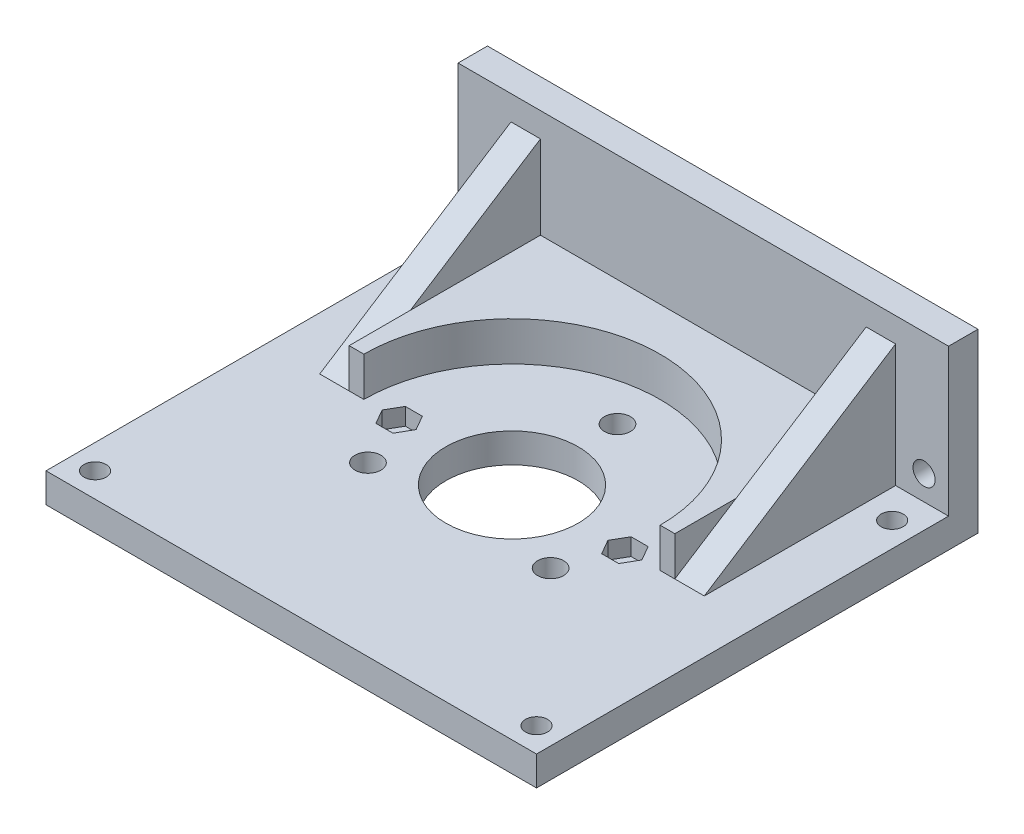
SolidWorks part; units mm, degrees
ref_plane "Front Plane" through (0, 0, 0) normal (0, 0, 1) x (1, 0, 0)
ref_plane "Top Plane" through (0, 0, 0) normal (0, 1, 0) x (1, 0, 0)
ref_plane "Right Plane" through (0, 0, 0) normal (1, 0, 0) x (0, 0, -1)
sketch "Sketch1" plane through (0, 0, 0) normal (0, 1, 0) x (1, 0, 0)
  line L0 (0, 0) -> (0, 21.5) construction
  line L1 (0, 0) -> (23.0125, 0) construction
  line L2 (-45, -40) -> (-45, -45) construction
  line L3 (50, 45) -> (-50, 45)
  line L4 (50, 45) -> (50, -45)
  line L5 (50, -45) -> (-50, -45)
  line L6 (-50, 45) -> (-50, -45)
  line L7 (-45, -40) -> (-50, -40) construction
  line L8 (-45, 32.5) -> (-50, 32.5) construction
  line L9 (-45, 32.5) -> (-45, 45) construction
  circle A0 centre (0, 0) radius 13.5
  circle A1 centre (0, 0) radius 23.0125 construction
  circle A2 centre (0, 0) radius 21.5 construction
  circle A4 centre (0, 21.5) radius 2.65
  circle A5 centre (23.0125, 0) radius 1.65
  circle A6 centre (-23.0125, 0) radius 1.65
  circle A7 centre (18.6195, -10.75) radius 2.65
  circle A8 centre (-18.6195, -10.75) radius 2.65
  circle A9 centre (-45, -40) radius 2.25
  circle A10 centre (-45, 32.5) radius 2.25
  circle A11 centre (45, 32.5) radius 2.25
  circle A12 centre (45, -40) radius 2.25
  point P24 (-50, 0)
  point P25 (0, 45)
  dimension "D1" = 27
  dimension "D2" = 46.025
  dimension "D3" = 43
  dimension "D4" = 4.5
  dimension "D5" = 5.3
  dimension "D6" = 3.3
  dimension "D9" = 5
  dimension "D11" = 12.5
  dimension "D12" = 100
  dimension "D13" = 90
  dimension "D7" = 2
  dimension "D8" = 3
extrude "Boss-Extrude1" add sketch "Sketch1" along normal blind 6
ref_plane "Plane4" through (0, 6, 0) normal (0, 1, 0) x (1, 0, 0)
sketch "Sketch2" plane through (0, 6, 0) normal (0, 1, 0) x (1, 0, 0)
  line L0 (-30.2, 0) -> (-33.2, 0)
  line L1 (-33.2, 0) -> (-33.2, 39)
  line L2 (50, 45) -> (-50, 45) construction
  line L3 (50, 45) -> (-50, 45) construction
  line L4 (-33.2, 39) -> (-33.2, 45) construction
  line L5 (-33.2, 39) -> (33.2, 39)
  line L6 (0, 0) -> (0, 9.2302) construction
  line L7 (33.2, 0) -> (33.2, 39)
  line L8 (30.2, 0) -> (33.2, 0)
  arc A0 (30.2, 0) -> (-30.2, 0) centre (0, 0) ccw
  point P13 (0, 39)
  dimension "D2" = 60.4
  dimension "D1" = 3
  dimension "D3" = 6
extrude "Boss-Extrude2" add sketch "Sketch2" along normal blind 8
sketch "Sketch3" plane through (0, 6, 0) normal (0, 1, 0) x (1, 0, 0)
  line L0 (33.2, 39) -> (-33.2, 39) construction
  line L1 (50, 39) -> (-50, 39)
  line L2 (50, 39) -> (50, 45)
  line L3 (50, 45) -> (-50, 45)
  line L4 (-50, 39) -> (-50, 45)
  line L5 (50, 45) -> (-50, 45) construction
  line L6 (33.2, 39) -> (-33.2, 39) construction
  line L7 (50, 45) -> (-50, 45) construction
  point P8 (0, 45)
  point P9 (0, 45)
extrude "Boss-Extrude3" add sketch "Sketch3" along normal blind 30
ref_plane "Plane5" through (0, 0, -39) normal (0, 0, 1) x (1, 0, 0)
sketch "Sketch7" plane through (0, 0, -39) normal (0, 0, 1) x (1, 0, 0)
  line L0 (-50, 36) -> (-50, 6) construction
  line L1 (-50, 6) -> (-33.2, 6) construction
  line L2 (-50, 36) -> (-50, 6) construction
  line L3 (-50, 6) -> (-33.2, 6) construction
  line L4 (-45, 11) -> (-50, 11) construction
  line L5 (-45, 11) -> (-45, 6) construction
  line L6 (0, 0) -> (0, 30.8351) construction
  circle A0 centre (-45, 11) radius 2.25
  circle A1 centre (45, 11) radius 2.25
  dimension "D1" = 4.5
  dimension "D2" = 5
extrude "Cut-Extrude1" cut sketch "Sketch7" against normal up to next
ref_plane "Plane6" through (0, 6, 0) normal (0, 1, 0) x (1, 0, 0)
sketch "Sketch8" plane through (0, 6, 0) normal (0, 1, 0) x (1, 0, 0)
  line L0 (19.5484, 0) -> (21.2804, -3)
  line L1 (-19.5484, 0) -> (-21.2804, 3)
  line L2 (-21.2804, 3) -> (-24.7446, 3)
  line L3 (-24.7446, 3) -> (-26.4766, 0)
  line L4 (-26.4766, 0) -> (-24.7446, -3)
  line L5 (-24.7446, -3) -> (-21.2804, -3)
  line L6 (-21.2804, -3) -> (-19.5484, 0)
  line L7 (21.2804, -3) -> (24.7446, -3)
  line L8 (24.7446, -3) -> (26.4766, 0)
  line L9 (26.4766, 0) -> (24.7446, 3)
  line L10 (24.7446, 3) -> (21.2804, 3)
  line L11 (21.2804, 3) -> (19.5484, 0)
  circle A0 centre (-23.0125, 0) radius 1.65 construction
  circle A1 centre (-23.0125, 0) radius 1.65 construction
  circle A2 centre (0, 0) radius 23.0125 construction
  circle A3 centre (-23.0125, 0) radius 3 construction
  point P6 (-23.0125, 3)
  dimension "D1" = 6
  dimension "D2" = 2
extrude "Cut-Extrude2" cut sketch "Sketch8" against normal blind 3.5
ref_plane "Plane7" through (-33.2, 0, 0) normal (-1, 0, 0) x (0, 0, 1)
sketch "Sketch9" plane through (-33.2, 0, 0) normal (-1, 0, 0) x (0, 0, 1)
  line L0 (-39, 6) -> (45, 6) construction
  line L1 (-39, 36) -> (-39, 6) construction
  line L2 (-39, 6) -> (45, 6) construction
  line L3 (-39, 36) -> (-39, 6) construction
  line L4 (0, 14) -> (0, 6) construction
  line L5 (0, 14) -> (0, 6) construction
  line L6 (-39, 6) -> (-39, 31)
  line L7 (0, 6) -> (-39, 31)
  line L8 (-39, 6) -> (0, 6)
  dimension "D1" = 25
extrude "Boss-Extrude4" add sketch "Sketch9" along normal blind 6
mirror "Mirror1" about plane through (0, 0, 0) normal (1, 0, 0) of "Boss-Extrude4"
